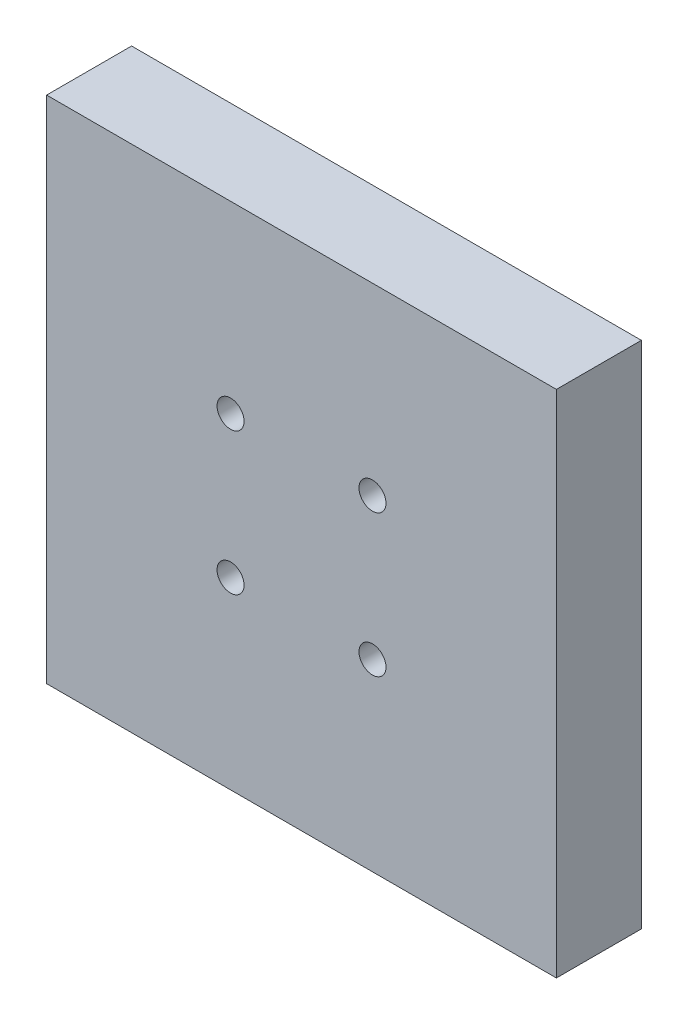
SolidWorks part; units mm, degrees
ref_plane "Front Plane" through (0, 0, 0) normal (0, 0, 1) x (1, 0, 0)
ref_plane "Top Plane" through (0, 0, 0) normal (0, 1, 0) x (1, 0, 0)
ref_plane "Right Plane" through (0, 0, 0) normal (1, 0, 0) x (0, 0, -1)
sketch "Sketch1" plane through (0, 0, 0) normal (0, 0, 1) x (1, 0, 0)
  line L0 (55, 0) -> (-55, 0) construction
  line L1 (-38.1, -38.1) -> (38.1, -38.1)
  line L2 (-38.1, -38.1) -> (-38.1, 38.1)
  line L3 (-38.1, 38.1) -> (38.1, 38.1)
  line L4 (38.1, -38.1) -> (38.1, 38.1)
  line L5 (-38.1, -38.1) -> (38.1, 38.1) construction
  line L6 (-38.1, 38.1) -> (38.1, -38.1) construction
  line L7 (-12.7, 38.1) -> (12.7, 38.1)
  line L8 (-12.7, 38.1) -> (-12.7, 44.45)
  line L9 (-12.7, 44.45) -> (12.7, 44.45)
  line L10 (12.7, 38.1) -> (12.7, 44.45)
  line L11 (-12.7, -44.45) -> (12.7, -44.45)
  line L12 (12.7, -38.1) -> (12.7, -44.45)
  line L13 (-12.7, -38.1) -> (12.7, -38.1)
  line L14 (-12.7, -38.1) -> (-12.7, -44.45)
  point P0 (0, 0)
  point P10 (0, 44.45)
  point P11 (0, 38.1)
  point P18 (0, -38.1)
  point P19 (0, -44.45)
  dimension "D1" = 76.2
  dimension "D2" = 76.2
  dimension "D3" = 25.4
  dimension "D4" = 6.35
extrude "Boss-Extrude1" add sketch "Sketch1" along normal blind 12.7 contours L1 L4 L3 L2 | L11 L12 L13 L14 | L9 L10 L7 L8
sketch "Sketch2" plane through (0, 0, 12.7) normal (0, 0, 1) x (1, 0, 0)
  line L0 (55, 0) -> (-55, 0) construction
  line L1 (-10.6066, -10.6066) -> (10.6066, -10.6066)
  line L2 (-10.6066, -10.6066) -> (-10.6066, 10.6066)
  line L3 (-10.6066, 10.6066) -> (10.6066, 10.6066)
  line L4 (10.6066, -10.6066) -> (10.6066, 10.6066)
  line L5 (-10.6066, -10.6066) -> (10.6066, 10.6066) construction
  line L6 (-10.6066, 10.6066) -> (10.6066, -10.6066) construction
  line L7 (0, -55) -> (0, 55) construction
  circle A0 centre (10.6066, 10.6066) radius 2.0193
  circle A1 centre (10.6066, -10.6066) radius 2.0193
  circle A2 centre (-10.6066, -10.6066) radius 2.0193
  circle A3 centre (-10.6066, 10.6066) radius 2.0193
  point P0 (0, 0)
  dimension "D2" = 4.0386
  dimension "D1" = 30
extrude "Cut-Extrude1" cut sketch "Sketch2" against normal through all contours A3 | A0 | A1 | A2
